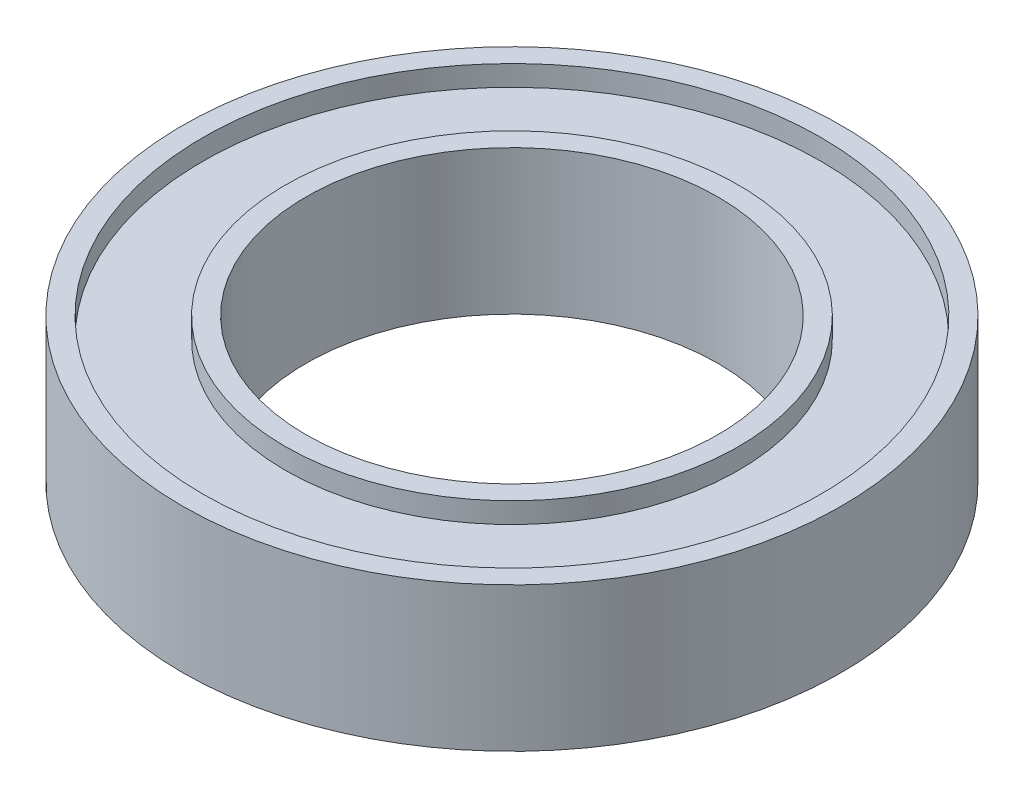
SolidWorks part; units mm, degrees
ref_plane "Front Plane" through (0, 0, 0) normal (0, 0, 1) x (1, 0, 0)
ref_plane "Top Plane" through (0, 0, 0) normal (0, 1, 0) x (1, 0, 0)
ref_plane "Right Plane" through (0, 0, 0) normal (1, 0, 0) x (0, 0, -1)
sketch "Sketch1" plane through (0, 0, 0) normal (0, 1, 0) x (1, 0, 0)
  circle A0 centre (0, 0) radius 16
  circle A1 centre (0, 0) radius 10
extrude "Boss-Extrude1" add sketch "Sketch1" along normal blind 7
sketch "Sketch2" plane through (0, 7, 0) normal (0, 1, 0) x (1, 0, 0)
  circle A0 centre (0, 0) radius 15
  circle A1 centre (0, 0) radius 11
extrude "Cut-Extrude1" cut sketch "Sketch2" against normal blind 1
sketch "Sketch3" plane through (0, 0, 0) normal (0, -1, 0) x (1, 0, 0)
  circle A0 centre (0, 0) radius 15
  circle A1 centre (0, 0) radius 11
extrude "Cut-Extrude2" cut sketch "Sketch3" against normal blind 1
